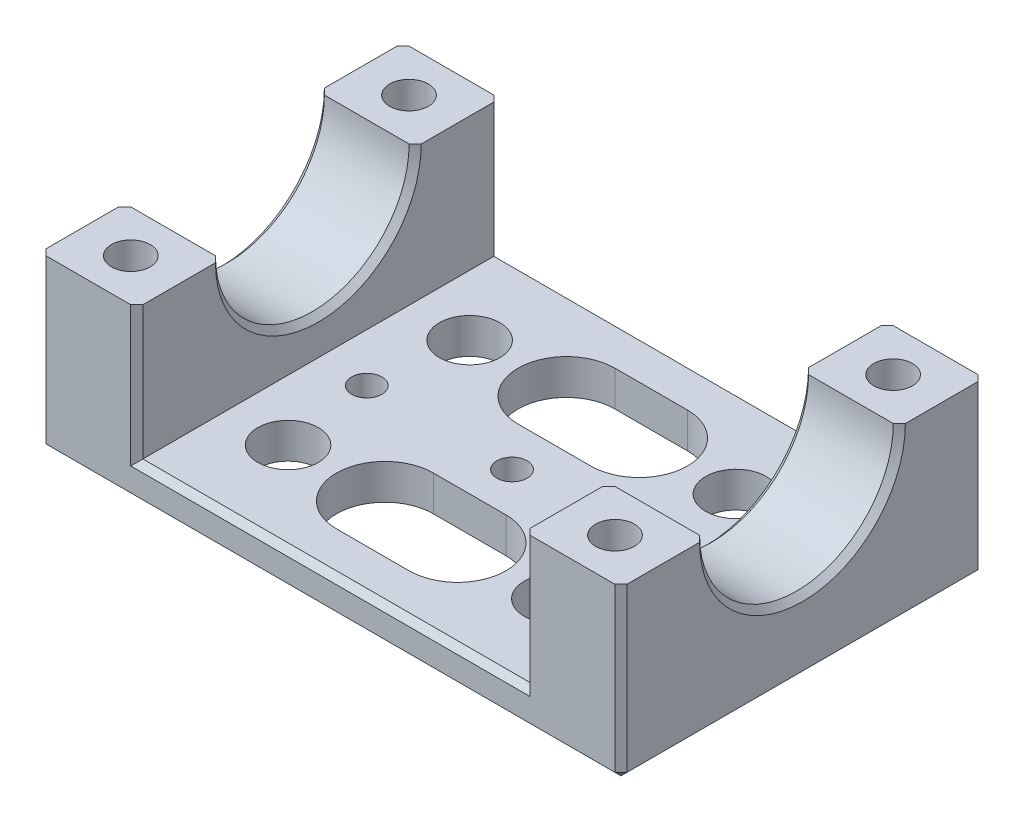
SolidWorks part; units mm, degrees
material "1060 Alloy"
ref_plane "Front Plane" through (0, 0, 0) normal (0, 0, 1) x (1, 0, 0)
ref_plane "Top Plane" through (0, 0, 0) normal (0, 1, 0) x (1, 0, 0)
ref_plane "Right Plane" through (0, 0, 0) normal (1, 0, 0) x (0, 0, -1)
sketch "Sketch2" plane through (0, 0, 0) normal (0, 1, 0) x (1, 0, 0)
  line L1 (16, -15) -> (-16, -15)
  line L2 (16, -15) -> (16, 15)
  line L3 (16, 15) -> (-16, 15)
  line L4 (-16, -15) -> (-16, 15)
  line L5 (16, -15) -> (-16, 15) construction
  line L6 (16, 15) -> (-16, -15) construction
  point P0 (0, 0)
  dimension "D1" = 30
  dimension "D2" = 32
extrude "Boss-Extrude1" add sketch "Sketch2" along normal blind 2.9227
sketch "Sketch3" plane through (0, 2.9227, 0) normal (0, 1, 0) x (1, 0, 0)
  line L0 (-16, 0) -> (16, 0) construction
  line L3 (-16, 15) -> (-16, -15) construction
  line L4 (-24, 15) -> (-16, 15)
  line L5 (-24, 15) -> (-24, -15)
  line L6 (-24, -15) -> (-16, -15)
  line L7 (-16, 15) -> (-16, -15)
  line L8 (-24, 15) -> (-16, -15) construction
  line L9 (-24, -15) -> (-16, 15) construction
  line L10 (24, -15) -> (16, -15)
  line L11 (24, -15) -> (24, 15)
  line L12 (24, 15) -> (16, 15)
  line L13 (16, -15) -> (16, 15)
  line L14 (24, -15) -> (16, 15) construction
  line L15 (24, 15) -> (16, -15) construction
  line L16 (16, -15) -> (16, 15) construction
  point P2 (-22.5, 0)
  point P4 (26.5258, 0)
  point P5 (0, 0)
  point P6 (-20, 0)
  point P11 (0, 0)
  point P12 (20, 0)
  point P17 (0, 0)
  point P19 (0, 0)
  point P20 (29.8877, 0)
  point P21 (22.5, 0)
  dimension "D1" = 8
  dimension "D2" = 30
  dimension "D3" = 8
extrude "Boss-Extrude2" add sketch "Sketch3" along normal blind 25 and the other way up to surface (2.9227 mm away) other way up to face at (0, 0, 0)
sketch "Sketch4" plane through (24, 0, 0) normal (1, 0, 0) x (0, 0, -1)
  line L0 (-15, 13.9613) -> (15, 13.9613) construction
  line L1 (-15, 27.9227) -> (-15, 0) construction
  line L2 (15, 27.9227) -> (15, 0) construction
  circle A0 centre (0, 13.9613) radius 8
  dimension "D1" = 16
extrude "Cut-Extrude1" cut sketch "Sketch4" against normal through all both and the other way through all
hole_wizard "M3x0.5 Tapped Hole1" positions "Sketch5" profile "Sketch6" tap size "M3x0.5" standard "ANSI Metric" end condition through all
sketch "Sketch5" plane through (0, 2.9227, 0) normal (0, 1, 0) x (1, 0, 0)
  line L0 (-16, 0) -> (16, 0) construction
  line L1 (-16, -15) -> (-16, 15) construction
  line L2 (16, -15) -> (16, 15) construction
  point P8 (0, 0)
  point P11 (-12, 0)
  point P13 (12, 0)
  point P16 (0, 0)
  dimension "D1" = 12
  dimension "D2" = 12
sketch "Sketch6" plane through (12, 2.9227, 0) normal (1, 0, 0) x (0, 0, 1)
  line L0 (0, 0) -> (0, 2.9227)
  line L1 (0, 2.9227) -> (1.25, 2.9227)
  line L2 (1.25, 2.9227) -> (1.25, 0)
  line L5 (1.25, 0) -> (0, 0)
  line L11 (0, -6.35) -> (0, 107.95) construction
  dimension "Thru Tap Drill Dia." = 2.5
  dimension "Thru Tap Drill Depth" = 2.9227
cosmetic thread "Hole Thread2" parameters "D2"=3
cosmetic thread "Hole Thread3" parameters "D2"=3
cosmetic thread "Hole Thread4" parameters "D2"=3
sketch "Sketch7" plane through (0, 2.9227, 0) normal (0, 1, 0) x (1, 0, 0)
  line L0 (-16, 0) -> (16, 0) construction
  line L1 (-3, 7.5) -> (3, 7.5) construction
  line L2 (-3, 11.5) -> (3, 11.5)
  line L3 (-16, -15) -> (-16, 15) construction
  line L4 (16, -15) -> (16, 15) construction
  line L5 (-16, 7.5) -> (16, 7.5) construction
  line L6 (-16, 15) -> (-16, -15) construction
  line L7 (-16, -7.5) -> (16, -7.5) construction
  line L8 (-3, 3.5) -> (3, 3.5)
  line L9 (-3, -7.5) -> (3, -7.5) construction
  line L10 (-3, -3.5) -> (3, -3.5)
  line L11 (-3, -11.5) -> (3, -11.5)
  circle A0 centre (-11, 7.5) radius 2.5
  circle A1 centre (-11, -7.5) radius 2.5
  circle A8 centre (11, -7.5) radius 2.5
  circle A9 centre (11, 7.5) radius 2.5
  circle A10 centre (0, 7.5) radius 2.5 [skipped]
  circle A11 centre (0, -7.5) radius 2.5 [skipped]
  circle A12 centre (5.5, 7.5) radius 2.5 [skipped]
  circle A13 centre (-5.5, 7.5) radius 2.5 [skipped]
  circle A14 centre (-5.5, -7.5) radius 2.5 [skipped]
  circle A15 centre (5.5, -7.5) radius 2.5 [skipped]
  arc A16 (-3, 11.5) -> (-3, 3.5) centre (-3, 7.5) ccw
  arc A17 (3, 3.5) -> (3, 11.5) centre (3, 7.5) ccw
  arc A18 (-3, -3.5) -> (-3, -11.5) centre (-3, -7.5) ccw
  arc A19 (3, -11.5) -> (3, -3.5) centre (3, -7.5) ccw
  point P17 (0, 7.5)
  point P25 (0, -7.5)
  point P46 (0, 0)
  point P47 (0, 0)
  dimension "D3" = 5
  dimension "D5" = 5
  dimension "D8" = 8
  dimension "D1" = 7.5
  dimension "D2" = 7.5
  dimension "D4" = 5
  dimension "D7" = 5
  dimension "D9" = 8
  dimension "D10" = 8
  dimension "D11" = 8
  dimension "D6" = 5
extrude "Cut-Extrude2" cut sketch "Sketch7" against normal through all
sketch "Sketch8" plane through (24, 0, 0) normal (1, 0, 0) x (0, 0, -1)
  line L0 (-15, 0) -> (-15, 27.9227) construction
  line L1 (-15, 13.9613) -> (15, 13.9613)
  line L2 (-15, 13.9613) -> (-15, 32.9227)
  line L3 (-15, 32.9227) -> (15, 32.9227)
  line L4 (15, 13.9613) -> (15, 32.9227)
  line L5 (15, 0) -> (15, 27.9227) construction
  line L6 (-15, 27.9227) -> (15, 27.9227) construction
  point P6 (12.5, 13.9613)
  dimension "D1" = 5
extrude "Cut-Extrude3" cut sketch "Sketch8" against normal through all
hole_wizard "M3 Clearance Hole1" positions "Sketch11" profile "Sketch12" hole size "M3" standard "ANSI Metric" end condition through all
sketch "Sketch11" plane through (0, 0, 0) normal (0, -1, 0) x (-1, 0, 0)
  line L1 (-20, 11.49) -> (20, 11.49) construction
  line L2 (-20, 11.49) -> (-20, -11.49) construction
  line L3 (-20, -11.49) -> (20, -11.49) construction
  line L4 (20, 11.49) -> (20, -11.49) construction
  line L5 (-24, 15) -> (-24, -15) construction
  line L6 (24, -15) -> (24, 15) construction
  line L7 (-24, 15) -> (24, 15) construction
  line L8 (24, -15) -> (-24, -15) construction
  point P1 (-20, 11.49)
  point P2 (20, -11.49)
  point P55 (-20, -11.49)
  point P56 (20, 11.49)
  dimension "D1" = 4
  dimension "D2" = 4
  dimension "D3" = 3.51
  dimension "D4" = 3.51
sketch "Sketch12" plane through (20, 0, -11.49) normal (1, 0, 0) x (0, 0, -1)
  line L0 (0, 0) -> (0, 13.9613)
  line L1 (0, 13.9613) -> (1.6, 13.9613)
  line L2 (1.6, 13.9613) -> (1.6, 0)
  line L5 (1.6, 0) -> (0, 0)
  line L11 (0, -6.35) -> (0, 107.95) construction
  dimension "Thru Hole Dia." = 3.2
  dimension "Thru Hole Depth" = 13.9613
chamfer "Chamfer1" distance 0.5 angle 45 18 edges at (-16, 5.9613, 0) (-24, 5.9613, 0) (24, 0, 0) (24, 6.9807, 15) (-24, 6.9807, 15) (-24, 0, 0) (-24, 6.9807, -15) (24, 6.9807, -15) (-16, 8.442, 15) (0, 2.9227, 15) (16, 8.442, 15) (24, 5.9613, 0) (16, 5.9613, 0) (-16, 8.442, -15) (0, 2.9227, -15) (16, 8.442, -15) (0, 0, 15) (0, 0, -15)
sketch "Sketch13" plane through (0, 0, 0) normal (0, -1, 0) x (1, 0, 0)
  circle A0 centre (20, -11.49) radius 3
  circle A1 centre (-20, -11.49) radius 3
  circle A2 centre (-20, 11.49) radius 3
  circle A3 centre (20, 11.49) radius 3
  dimension "D1" = 6
  dimension "D2" = 6
  dimension "D3" = 6
  dimension "D4" = 6
extrude "Cut-Extrude4" cut sketch "Sketch13" against normal blind 4
